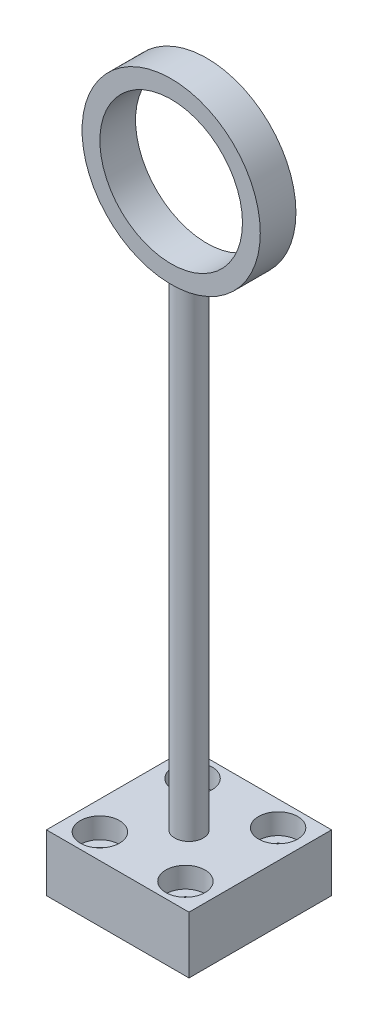
SolidWorks part; units mm, degrees
ref_plane "前视基准面" through (0, 0, 0) normal (0, 0, 1) x (1, 0, 0)
ref_plane "上视基准面" through (0, 0, 0) normal (0, 1, 0) x (1, 0, 0)
ref_plane "右视基准面" through (0, 0, 0) normal (1, 0, 0) x (0, 0, -1)
sketch "草图1" plane through (0, 0, 0) normal (0, 0, 1) x (1, 0, 0)
  circle A0 centre (0, 0) radius 10
  circle A1 centre (0, 0) radius 12.5
  dimension "D1" = 20
  dimension "D2" = 25
extrude "凸台-拉伸1" add sketch "草图1" along normal blind 5
ref_plane "基准面1" through (0, -80, 0) normal (0, 1, 0) x (1, 0, 0)
sketch "草图2" plane through (0, -80, 0) normal (0, 1, 0) x (1, 0, 0)
  circle A0 centre (0, -2.5) radius 2
  dimension "D1" = 4
  dimension "D2" = 2.5
extrude "凸台-拉伸2" add sketch "草图2" along normal up to surface (67.5 mm away)
sketch "草图3" plane through (0, -80, 0) normal (0, -1, 0) x (1, 0, 0)
  line L1 (-10, 12.5) -> (10, 12.5)
  line L2 (-10, 12.5) -> (-10, -7.5)
  line L3 (-10, -7.5) -> (10, -7.5)
  line L4 (10, 12.5) -> (10, -7.5)
  line L5 (0, -7.5) -> (0, 12.5) construction
  line L6 (-10, 2.5) -> (10, 2.5) construction
  point P0 (0, 2.5)
  dimension "D1" = 20
  dimension "D2" = 20
extrude "凸台-拉伸3" add sketch "草图3" along normal blind 8
hole_wizard "M2.5 六角凹头螺钉的柱形沉头孔1" positions "草图11" profile "草图12" counterbore size "M2.5" standard "ISO" end condition through all
sketch "草图11" plane through (0, -80, 0) normal (0, 1, 0) x (1, 0, 0)
  line L1 (-10, 7.5) -> (10, 7.5) construction
  line L2 (10, -12.5) -> (-10, -12.5) construction
  point P0 (-6, 4)
  point P2 (6, 4)
  point P4 (6, -9)
  point P6 (-6, -9)
  point P14 (-6, 4.0983)
  point P17 (0, 0)
  point P18 (0, 0)
  point P19 (0, 0)
  point P24 (0, 0)
  dimension "D1" = 6
  dimension "D2" = 6
  dimension "D3" = 3.5
  dimension "D4" = 3.5
  dimension "D5" = 3.5
sketch "草图12" plane through (-6, -80, -4) normal (1, 0, 0) x (0, 0, 1)
  line L0 (0, 0) -> (0, 8)
  line L1 (0, 8) -> (1.45, 8)
  line L3 (1.45, 8) -> (1.45, 2.9)
  line L4 (1.45, 2.9) -> (2.75, 2.9)
  line L5 (2.75, 2.9) -> (2.75, 0)
  line L7 (2.75, 0) -> (0, 0)
  line L11 (0, -6.35) -> (0, 107.95) construction
  dimension "通孔孔直径" = 2.9
  dimension "通孔孔深度" = 8
  dimension "柱形沉头孔直径" = 5.5
  dimension "柱形沉头孔深度" = 2.9
